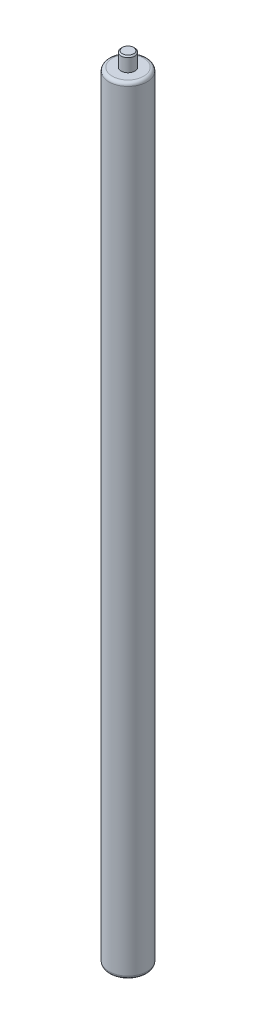
SolidWorks part; units mm, degrees
material "Plain Carbon Steel"
ref_plane "Front Plane" through (0, 0, 0) normal (0, 0, 1) x (1, 0, 0)
ref_plane "Top Plane" through (0, 0, 0) normal (0, 1, 0) x (1, 0, 0)
ref_plane "Right Plane" through (0, 0, 0) normal (1, 0, 0) x (0, 0, -1)
sketch "Sketch1" plane through (0, 0, 0) normal (0, 1, 0) x (1, 0, 0)
  circle A0 centre (0, 0) radius 11.049
  dimension "D1" = 22.098
extrude "Boss-Extrude1" add sketch "Sketch1" along normal blind 452.12
sketch "Sketch2" plane through (0, 452.12, 0) normal (0, 1, 0) x (1, 0, 0)
  circle A0 centre (0, 0) radius 4
  dimension "D1" = 8
extrude "Boss-Extrude2" add sketch "Sketch2" along normal blind 8.382
chamfer "Chamfer1" distance 0.762 angle 45 1 edges at (0, 460.502, 4)
fillet "Fillet1" radius 1.905 2 edges at (0, 0, 11.049) (0, 452.12, 11.049)
sketch "Sketch3" plane through (0, 0, 0) normal (0, -1, 0) x (1, 0, 0)
  circle A0 centre (0, 0) radius 4.953
  dimension "D1" = 9.906
extrude "Cut-Extrude1" cut sketch "Sketch3" against normal blind 431.8
